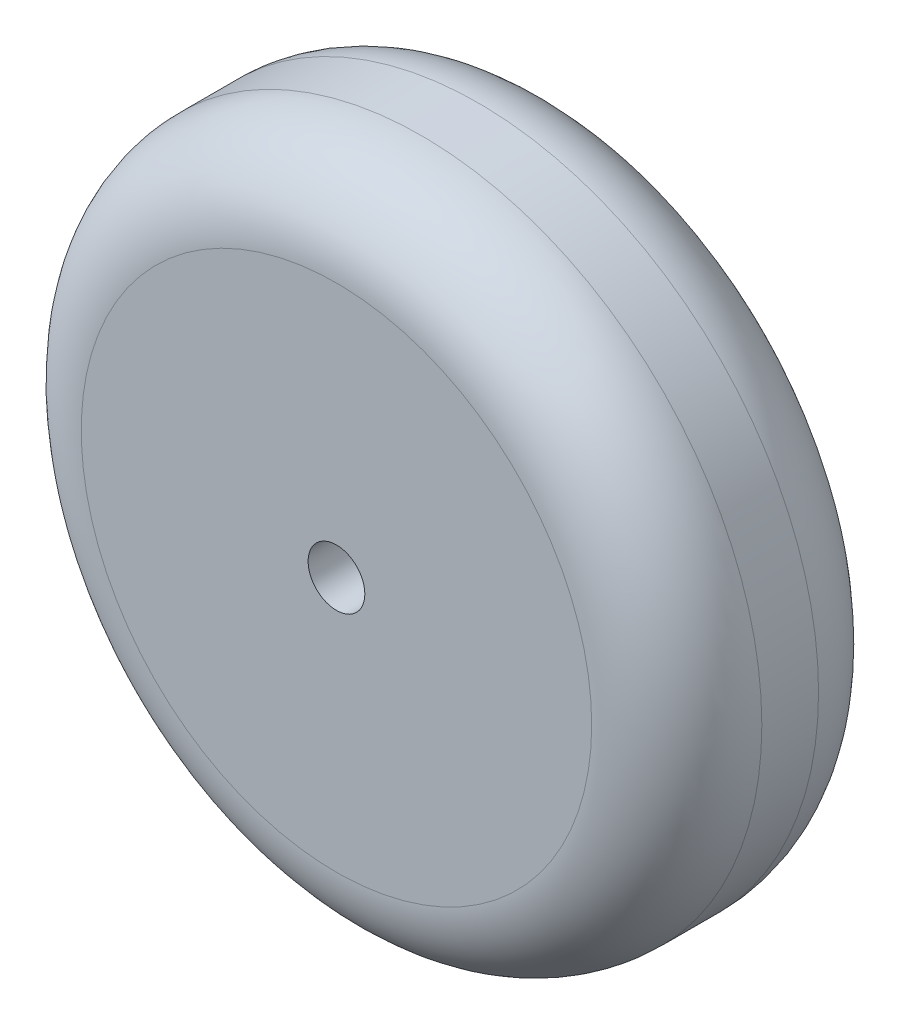
SolidWorks part; units mm, degrees
ref_plane "Front Plane" through (0, 0, 0) normal (0, 0, 1) x (1, 0, 0)
ref_plane "Top Plane" through (0, 0, 0) normal (0, 1, 0) x (1, 0, 0)
ref_plane "Right Plane" through (0, 0, 0) normal (1, 0, 0) x (0, 0, -1)
sketch "Sketch1" plane through (0, 0, 0) normal (0, 0, 1) x (1, 0, 0)
  circle A0 centre (0, 0) radius 30
  dimension "D1" = 60
extrude "Boss-Extrude1" add sketch "Sketch1" along normal blind 20
sketch "Sketch2" plane through (0, 0, 20) normal (0, 0, 1) x (1, 0, 0)
  circle A0 centre (0, 0) radius 2.5
  dimension "D1" = 5
extrude "Cut-Extrude1" cut sketch "Sketch2" against normal blind 20
fillet "Fillet1" radius 7.5 2 edges at (30, 0, 20) (30, 0, 0)
